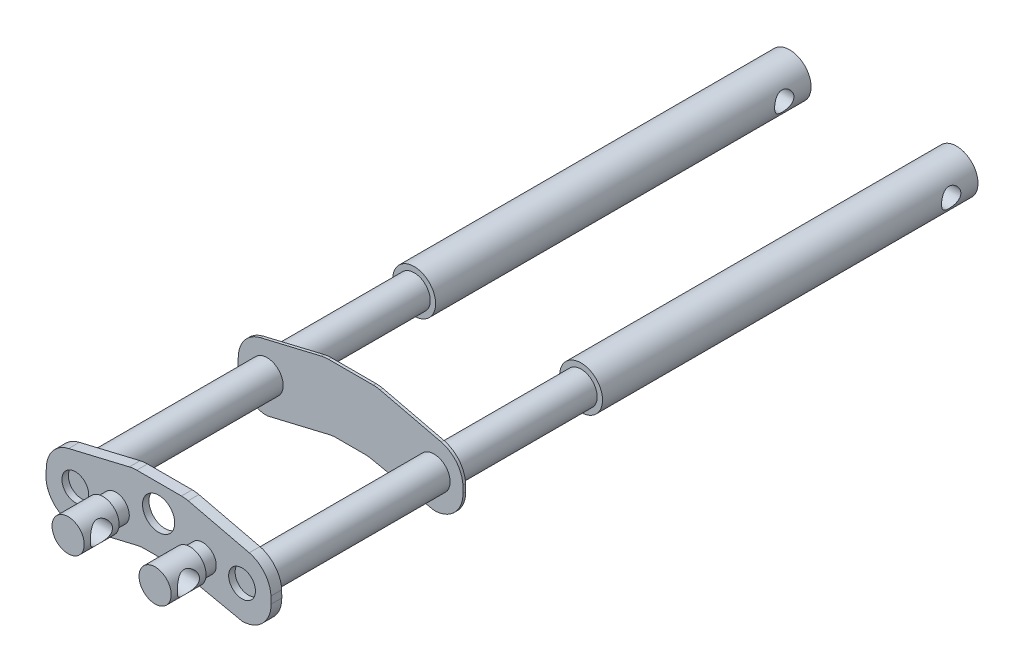
SolidWorks part; units mm, degrees
ref_plane "Front Plane" through (0, 0, 0) normal (0, 0, 1) x (1, 0, 0)
ref_plane "Top Plane" through (0, 0, 0) normal (0, 1, 0) x (1, 0, 0)
ref_plane "Right Plane" through (0, 0, 0) normal (1, 0, 0) x (0, 0, -1)
sketch "Sketch1" plane through (0, 0, 0) normal (0, 0, 1) x (1, 0, 0)
  line L3 (-89.5701, 21.4119) -> (-32.9907, 34.8583)
  line L4 (-110.2824, -3.3011) -> (-110.6709, -10.033)
  line L5 (-26.0542, 35.6712) -> (15.6172, 35.6712)
  line L6 (-29.5701, 35.6712) -> (-29.5701, 35.4645) construction
  line L7 (-83.3223, -38.5856) -> (-25.87, -24.9303)
  line L8 (99.0596, -3.3417) -> (99.1048, -9.9707)
  line L9 (78.7815, 21.4119) -> (21.86, 34.9396)
  line L10 (-5.6969, -24.1172) -> (-5.2185, 35.6712) construction
  line L14 (72.1054, -37.1546) -> (13.7685, -24.7711)
  line L15 (-18.9329, -24.1172) -> (7.5391, -24.1172)
  arc A0 (-83.3223, -38.5856) -> (-110.6709, -10.033) centre (-83.7157, -11.5885) cw
  arc A1 (-110.2824, -3.3011) -> (-89.5701, 21.4119) centre (-83.3273, -4.8565) cw
  arc A2 (-26.0542, 35.6712) -> (-32.9907, 34.8583) centre (-26.0542, 5.6712) ccw
  arc A3 (72.1054, -37.1546) -> (99.1048, -9.9707) centre (72.1054, -10.1546) ccw
  arc A4 (99.0596, -3.3417) -> (78.7815, 21.4119) centre (72.0963, -4.7474) ccw
  arc A5 (15.6172, 35.6712) -> (21.86, 34.9396) centre (15.6172, 8.6712) cw
  arc A6 (13.7685, -24.7711) -> (7.5391, -24.1172) centre (7.5391, -54.1172) ccw
  arc A7 (-25.87, -24.9303) -> (-18.9329, -24.1172) centre (-18.9329, -54.1172) cw
  circle A8 centre (-83.3273, -6.6562) radius 12.5
  circle A9 centre (72.0963, -6.6562) radius 12.5
  circle A10 centre (-5.6969, 10.6712) radius 15
  point P7 (-112.293, -38.144)
  point P10 (-109.1246, 16.7647)
  point P34 (10.6881, -24.1172)
  point P37 (-22.4491, -24.1172)
  point P38 (-83.3273, -6.6562)
  point P39 (72.0963, -6.6562)
  point P44 (-5.6969, 10.6712)
  dimension "D4" = 27
  dimension "D1" = 25
  dimension "D2" = 25
  dimension "D7" = 104.6852
  dimension "D3" = 30
  dimension "D6" = 155.4235
  dimension "D5" = 25
extrude "Boss-Extrude1" add sketch "Sketch1" along normal blind 10
sketch3d "3DSketch1"
  line L0 (-107.2874, -3.4739, 0) -> (-107.6759, -10.2059, 0)
  line L1 (-32.297, 31.9396, 0) -> (-88.8764, 18.4932, 0)
  line L2 (15.6172, 32.6712, 0) -> (-26.0542, 32.6712, 0)
  line L3 (78.0625, 18.4992, 0) -> (21.1664, 32.0209, 0)
  line L4 (96.1049, -9.9911, 0) -> (96.0602, -3.4321, 0)
  line L5 (14.3914, -21.8365, 0) -> (72.4111, -34.1526, 0)
  line L6 (-18.9329, -21.1172, 0) -> (7.5391, -21.1172, 0)
  line L7 (-83.6859, -35.5884, 0) -> (-26.5638, -22.0116, 0)
  line L8 (-107.2874, -3.4739, 0) -> (-107.6759, -10.2059, 0)
  line L9 (-32.297, 31.9396, 0) -> (-88.8764, 18.4932, 0)
  line L10 (15.6172, 32.6712, 0) -> (-26.0542, 32.6712, 0)
  line L11 (78.0625, 18.4992, 0) -> (21.1664, 32.0209, 0)
  line L12 (96.1049, -9.9911, 0) -> (96.0602, -3.4321, 0)
  line L13 (14.3914, -21.8365, 0) -> (72.4111, -34.1526, 0)
  line L14 (-18.9329, -21.1172, 0) -> (7.5391, -21.1172, 0)
  line L15 (-83.6859, -35.5884, 0) -> (-26.5638, -22.0116, 0)
  arc A0 (-88.8764, 18.4932, 0) -> (-107.2874, -3.4739, 0) centre (-83.3273, -4.8565, 0) ccw
  arc A1 (-26.0542, 32.6712, 0) -> (-32.297, 31.9396, 0) centre (-26.0542, 5.6712, 0) ccw
  arc A2 (21.1664, 32.0209, 0) -> (15.6172, 32.6712, 0) centre (15.6172, 8.6712, 0) ccw
  arc A3 (96.0602, -3.4321, 0) -> (78.0625, 18.4992, 0) centre (72.0963, -4.7474, 0) ccw
  arc A4 (72.4111, -34.1526, 0) -> (96.1049, -9.9911, 0) centre (72.1054, -10.1546, 0) ccw
  arc A5 (7.5391, -21.1172, 0) -> (14.3914, -21.8365, 0) centre (7.5391, -54.1172, 0) ccw
  arc A6 (-26.5638, -22.0116, 0) -> (-18.9329, -21.1172, 0) centre (-18.9329, -54.1172, 0) ccw
  arc A7 (-107.6759, -10.2059, 0) -> (-83.6859, -35.5884, 0) centre (-83.7157, -11.5885, 0) ccw
  arc A8 (-88.8764, 18.4932, 0) -> (-107.2874, -3.4739, 0) centre (-83.3273, -4.8565, 0) ccw
  arc A9 (-26.0542, 32.6712, 0) -> (-32.297, 31.9396, 0) centre (-26.0542, 5.6712, 0) ccw
  arc A10 (21.1664, 32.0209, 0) -> (15.6172, 32.6712, 0) centre (15.6172, 8.6712, 0) ccw
  arc A11 (96.0602, -3.4321, 0) -> (78.0625, 18.4992, 0) centre (72.0963, -4.7474, 0) ccw
  arc A12 (72.4111, -34.1526, 0) -> (96.1049, -9.9911, 0) centre (72.1054, -10.1546, 0) ccw
  arc A13 (7.5391, -21.1172, 0) -> (14.3914, -21.8365, 0) centre (7.5391, -54.1172, 0) ccw
  arc A14 (-26.5638, -22.0116, 0) -> (-18.9329, -21.1172, 0) centre (-18.9329, -54.1172, 0) ccw
  arc A15 (-107.6759, -10.2059, 0) -> (-83.6859, -35.5884, 0) centre (-83.7157, -11.5885, 0) ccw
  point P4 (-83.3273, -4.8565, 24)
  point P8 (-26.0542, 5.6712, 27)
  point P12 (15.6172, 8.6712, 24)
  point P16 (72.0963, -4.7474, 24)
  point P20 (72.1054, -10.1546, 24)
  point P24 (7.5391, -54.1172, -33)
  point P28 (-18.9329, -54.1172, -33)
  point P31 (-83.7157, -11.5885, 24)
  point P32 (-83.3273, -4.8565, 24)
  point P33 (-26.0542, 5.6712, 27)
  point P34 (15.6172, 8.6712, 24)
  point P35 (72.0963, -4.7474, 24)
  point P36 (72.1054, -10.1546, 24)
  point P37 (7.5391, -54.1172, -33)
  point P38 (-18.9329, -54.1172, -33)
  point P39 (-83.7157, -11.5885, 24)
  dimension "D1" = 3
extrude "Cut-Extrude1" cut sketch "3DSketch1" along direction (0, 0, -1) on the side against the normal blind 4
sketch "Sketch2" plane through (0, 0, 4) normal (0, 0, -1) x (-1, 0, 0)
  circle A0 centre (-72.0963, -6.6562) radius 15
  circle A2 centre (83.4901, -6.6562) radius 15
  dimension "D1" = 30
  dimension "D2" = 30
extrude "Boss-Extrude2" add sketch "Sketch2" along normal blind 310
sketch "Sketch3" plane through (0, 0, 0) normal (0, 1, 0) x (1, 0, 0)
  line L3 (0, 656) -> (0, 0) construction
  point P0 (0, 306)
  dimension "D1" = 350
ref_plane "Plane1" through (0, 0, -306) normal (0, 0, 1) x (1, 0, 0)
sketch "Sketch4" plane through (0, 0, -306) normal (0, 0, 1) x (1, 0, 0)
  circle A0 centre (-83.4901, -6.6562) radius 20
  circle A1 centre (72.0963, -6.6562) radius 20
  dimension "D1" = 40
  dimension "D2" = 40
extrude "Boss-Extrude3" add sketch "Sketch4" against normal blind 350
sketch "Sketch5" plane through (0, 0, 0) normal (1, 0, 0) x (0, 0, -1)
  line L0 (656, -6.6562) -> (631, -6.6562)
  line L1 (656, -26.6562) -> (656, 13.3438) construction
  circle A0 centre (631, -6.6562) radius 9
  dimension "D2" = 18
  dimension "D1" = 25
extrude "Cut-Extrude2" cut sketch "Sketch5" against normal mid plane 260
ref_plane "Plane2" through (0, 0, 10) normal (0, 0, 1) x (1, 0, 0)
sketch "Sketch7" plane through (0, 0, 10) normal (0, 0, 1) x (1, 0, 0)
  line L0 (-5.2185, 35.6712) -> (-5.6969, -24.1172) construction
  line L1 (15.6172, 35.6712) -> (-26.0542, 35.6712) construction
  line L2 (-18.9329, -24.1172) -> (7.5391, -24.1172) construction
  line L3 (-5.5386, -4.3275) -> (-45.5386, -4.3275) construction
  circle A0 centre (-45.5386, -4.3275) radius 12.5
  point P6 (-5.5386, -4.3275)
  dimension "D2" = 25
  dimension "D1" = 40
  dimension "D3" = 40
extrude "Boss-Extrude4" add sketch "Sketch7" along normal blind 12
ref_plane "Plane3" through (0, 0, 22) normal (0, 0, 1) x (1, 0, 0)
sketch "Sketch8" plane through (0, 0, 22) normal (0, 0, 1) x (1, 0, 0)
  circle A0 centre (-45.5386, -4.3275) radius 15
  dimension "D1" = 30
extrude "Boss-Extrude5" add sketch "Sketch8" along normal blind 32.5
ref_plane "Plane4" through (-45, 0, 0) normal (1, 0, 0) x (0, 0, -1)
ref_plane "Plane6" through (-45, 0, 0) normal (1, 0, 0) x (0, 0, -1)
sketch "Sketch15" plane through (-45, 0, 0) normal (1, 0, 0) x (0, 0, -1)
  line L0 (-22, -19.3275) -> (-22, 10.6725) construction
  line L1 (-54.5, 10.6725) -> (-54.5, -19.3275) construction
  line L2 (-22, -19.3275) -> (-22, 10.6725)
  line L3 (-54.5, 10.6725) -> (-54.5, -19.3275)
  line L4 (-54.5, -4.3275) -> (-22, -4.3275)
  circle A0 centre (-38.5, -4.3275) radius 10.3484
  point P4 (-38.5, -4.3275)
  dimension "D2" = 16
  dimension "D1" = 32.5
extrude "Cut-Extrude4" cut sketch "Sketch15" against normal mid plane 35 contours L4 A0 | L4 A0
ref_plane "Plane7" through (-5, 0, 0) normal (1, 0, 0) x (0, 0, -1)
mirror "Mirror5" about plane through (-5, 0, 0) normal (1, 0, 0) of "Boss-Extrude4", "Cut-Extrude4", "Boss-Extrude5"
ref_plane "Plane16" through (0, 0, -171.45) normal (0, 0, 1) x (1, 0, 0)
sketch "Sketch29" plane through (0, 0, -171.45) normal (0, 0, 1) x (1, 0, 0)
  line L16 (-83.3223, -38.5856) -> (-25.87, -24.9303)
  line L17 (-18.9329, -24.1172) -> (7.5391, -24.1172)
  line L18 (13.7685, -24.7711) -> (72.1054, -37.1546)
  line L19 (99.1048, -9.9707) -> (99.0596, -3.3417)
  line L20 (78.7815, 21.4119) -> (21.86, 34.9396)
  line L21 (15.6172, 35.6712) -> (-26.0542, 35.6712)
  line L22 (-32.9907, 34.8583) -> (-89.5701, 21.4119)
  line L23 (-110.2824, -3.3011) -> (-110.6709, -10.033)
  line L24 (-83.3223, -38.5856) -> (-25.87, -24.9303)
  line L25 (-18.9329, -24.1172) -> (7.5391, -24.1172)
  line L26 (13.7685, -24.7711) -> (72.1054, -37.1546)
  line L27 (99.1048, -9.9707) -> (99.0596, -3.3417)
  line L28 (78.7815, 21.4119) -> (21.86, 34.9396)
  line L29 (15.6172, 35.6712) -> (-26.0542, 35.6712)
  line L30 (-32.9907, 34.8583) -> (-89.5701, 21.4119)
  line L31 (-110.2824, -3.3011) -> (-110.6709, -10.033)
  circle A0 centre (72.0963, -6.6562) radius 14.986
  circle A1 centre (-83.3273, -6.6562) radius 14.986
  arc A18 (-110.6709, -10.033) -> (-83.3223, -38.5856) centre (-83.7157, -11.5885) ccw
  arc A19 (-18.9329, -24.1172) -> (-25.87, -24.9303) centre (-18.9329, -54.1172) ccw
  arc A20 (13.7685, -24.7711) -> (7.5391, -24.1172) centre (7.5391, -54.1172) ccw
  arc A21 (72.1054, -37.1546) -> (99.1048, -9.9707) centre (72.1054, -10.1546) ccw
  arc A22 (99.0596, -3.3417) -> (78.7815, 21.4119) centre (72.0963, -4.7474) ccw
  arc A23 (21.86, 34.9396) -> (15.6172, 35.6712) centre (15.6172, 8.6712) ccw
  arc A24 (-26.0542, 35.6712) -> (-32.9907, 34.8583) centre (-26.0542, 5.6712) ccw
  arc A25 (-89.5701, 21.4119) -> (-110.2824, -3.3011) centre (-83.3273, -4.8565) ccw
  arc A26 (-110.6709, -10.033) -> (-83.3223, -38.5856) centre (-83.7157, -11.5885) ccw
  arc A27 (-18.9329, -24.1172) -> (-25.87, -24.9303) centre (-18.9329, -54.1172) ccw
  arc A28 (13.7685, -24.7711) -> (7.5391, -24.1172) centre (7.5391, -54.1172) ccw
  arc A29 (72.1054, -37.1546) -> (99.1048, -9.9707) centre (72.1054, -10.1546) ccw
  arc A30 (99.0596, -3.3417) -> (78.7815, 21.4119) centre (72.0963, -4.7474) ccw
  arc A31 (21.86, 34.9396) -> (15.6172, 35.6712) centre (15.6172, 8.6712) ccw
  arc A32 (-26.0542, 35.6712) -> (-32.9907, 34.8583) centre (-26.0542, 5.6712) ccw
  arc A33 (-89.5701, 21.4119) -> (-110.2824, -3.3011) centre (-83.3273, -4.8565) ccw
  dimension "D1" = 29.972
  dimension "D2" = 29.972
  dimension "D3" = 0
  dimension "D4" = 59.7884
extrude "Boss-Extrude9" add sketch "Sketch29" along normal blind 2.54 contours L24 A27 L25 A28 L26 A29 L27 A30 L28 A31 L29 A32 L30 A33 L31 A26
ref_plane "Plane10" through (-5, 0, 0) normal (1, 0, 0) x (0, 0, -1)
